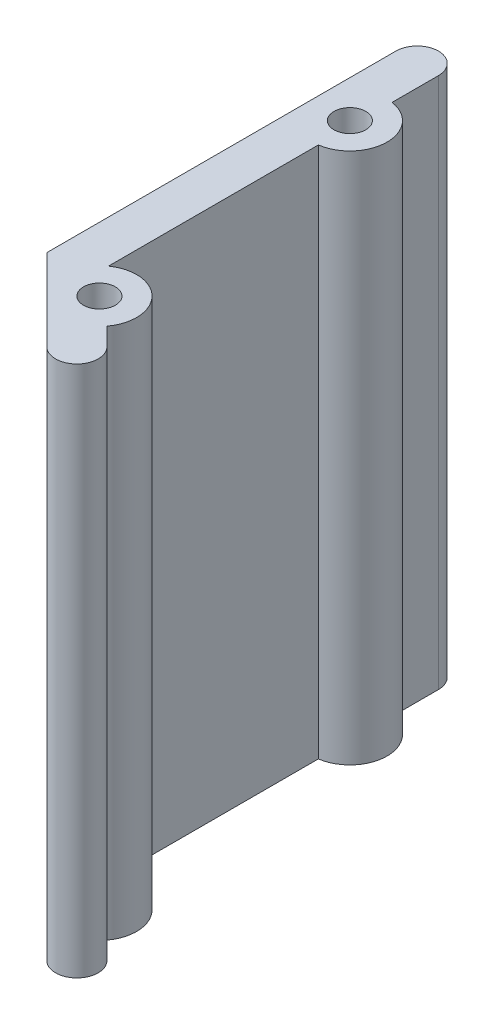
SolidWorks part; units mm, degrees
material "ABS"
ref_plane "Front Plane" through (0, 0, 0) normal (0, 0, 1) x (1, 0, 0)
ref_plane "Top Plane" through (0, 0, 0) normal (0, 1, 0) x (1, 0, 0)
ref_plane "Right Plane" through (0, 0, 0) normal (1, 0, 0) x (0, 0, -1)
sketch "Sketch1" plane through (0, 0, 0) normal (0, 1, 0) x (1, 0, 0)
  line L0 (0, 32) -> (0, 0) construction
  line L1 (0, 0) -> (7.0711, -7.0711) construction
  line L2 (-2, 32) -> (-2, -0.8284)
  line L3 (-2, -0.8284) -> (5.6569, -8.4853)
  line L4 (2, 32) -> (2, 0.8284)
  line L5 (2, 0.8284) -> (8.4853, -5.6569)
  arc A0 (-2, 32) -> (2, 32) centre (0, 32) cw
  arc A1 (5.6569, -8.4853) -> (8.4853, -5.6569) centre (7.0711, -7.0711) ccw
  dimension "D1" = 32
  dimension "D2" = 10
  dimension "D3" = 135
  dimension "D4" = 2
  dimension "D5" = 2
extrude "Boss-Extrude1" add sketch "Sketch1" along normal blind 50
sketch "Sketch5" plane through (0, 0, 0) normal (0, -1, 0) x (-1, 0, 0)
  line L0 (2, -0.8284) -> (-5.6569, -8.4853) construction
  line L1 (2, -0.8284) -> (-1.5355, -4.364) construction
  line L2 (-1.5355, -4.364) -> (-4.364, -1.5355) construction
  line L3 (-8.4853, -5.6569) -> (-2, 0.8284) construction
  line L4 (2, -0.8284) -> (2, 24.1716) construction
  line L5 (2, 24.1716) -> (-1.5, 24.1716) construction
  circle A0 centre (-4.0104, -1.8891) radius 1.5
  circle A1 centre (-1.5, 24.1716) radius 1.5
  circle A2 centre (-1.5, 24.1716) radius 3.5
  circle A3 centre (-4.0104, -1.8891) radius 3.5
  dimension "D1" = 3
  dimension "D2" = 3.5
  dimension "D3" = 5
  dimension "D4" = 25
  dimension "D5" = 3.5
  dimension "D6" = 2
extrude "Boss-Extrude2" add sketch "Sketch5" against normal through all contours A2 | A1 | A3 | A0
sketch "Sketch6" plane through (0, 0, 0) normal (0, -1, 0) x (-1, 0, 0)
  circle A1 centre (-4.0104, -1.8891) radius 1.5
  circle A2 centre (-1.5, 24.1716) radius 1.5
extrude "Cut-Extrude1" cut sketch "Sketch6" against normal blind 10
sketch "Sketch7" plane through (0, 50, 0) normal (0, 1, 0) x (1, 0, 0)
  circle A0 centre (4.0104, -1.8891) radius 1.5
  circle A1 centre (1.5, 24.1716) radius 1.5
extrude "Cut-Extrude2" cut sketch "Sketch7" against normal blind 10
